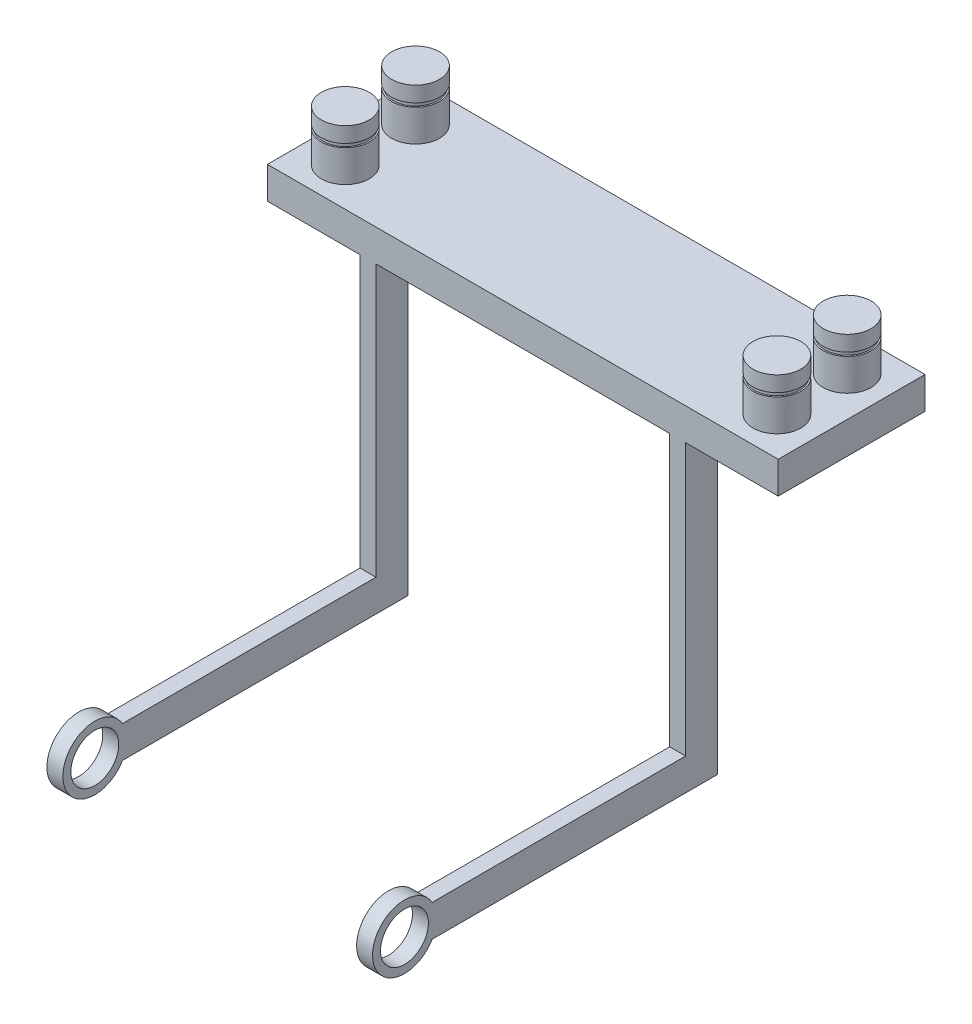
SolidWorks part; units mm, degrees
ref_plane "Front Plane" through (0, 0, 0) normal (0, 0, 1) x (1, 0, 0)
ref_plane "Top Plane" through (0, 0, 0) normal (0, 1, 0) x (1, 0, 0)
ref_plane "Right Plane" through (0, 0, 0) normal (1, 0, 0) x (0, 0, -1)
sketch "Sketch2" plane through (0, 0, 0) normal (0, 1, 0) x (1, 0, 0)
  line L1 (0, 0) -> (50.8, 0)
  line L2 (0, 0) -> (0, 29.21)
  line L3 (0, 29.21) -> (50.8, 29.21)
  line L4 (50.8, 0) -> (50.8, 29.21)
  dimension "D1" = 29.21
  dimension "D2" = 50.8
extrude "Boss-Extrude1" add sketch "Sketch2" along normal blind 6.35
sketch "Sketch4" plane through (0, 6.35, 0) normal (0, 1, 0) x (1, 0, 0)
  line L0 (0, 0) -> (50.8, 0) construction
  line L1 (50.8, 29.21) -> (0, 29.21) construction
  line L2 (50.8, 0) -> (50.8, 29.21) construction
  circle A0 centre (42.926, 7.62) radius 4.7625
  circle A1 centre (42.926, 21.59) radius 4.7625
  dimension "D1" = 9.525
  dimension "D2" = 9.525
  dimension "D3" = 7.62
  dimension "D4" = 7.62
  dimension "D5" = 7.874
  dimension "D6" = 7.874
extrude "Boss-Extrude2" add sketch "Sketch4" along normal blind 6.35
sketch "Sketch7" plane through (0, 12.7, 0) normal (0, 1, 0) x (1, 0, 0)
  line L0 (50.8, 29.21) -> (0, 29.21) construction
  line L1 (0, 0) -> (50.8, 0) construction
  line L2 (50.8, 0) -> (50.8, 29.21) construction
  circle A0 centre (42.926, 21.59) radius 4.4704
  circle A1 centre (42.926, 7.62) radius 4.4704
  dimension "D1" = 8.9408
  dimension "D2" = 8.9408
  dimension "D3" = 7.62
  dimension "D5" = 7.874
  dimension "D6" = 7.874
  dimension "D4" = 7.62
extrude "Boss-Extrude3" add sketch "Sketch7" along normal blind 0.7366
sketch "Sketch8" plane through (0, 13.4366, 0) normal (0, 1, 0) x (1, 0, 0)
  line L0 (50.8, 0) -> (50.8, 29.21) construction
  line L1 (50.8, 29.21) -> (0, 29.21) construction
  circle A0 centre (42.926, 21.59) radius 4.7625
  circle A1 centre (42.926, 7.62) radius 4.7625
  dimension "D1" = 9.525
  dimension "D2" = 9.525
  dimension "D3" = 7.874
  dimension "D4" = 7.62
extrude "Boss-Extrude4" add sketch "Sketch8" along normal blind 3.0734
sketch "Sketch11" plane through (0, 0, 0) normal (0, -1, 0) x (1, 0, 0)
  line L0 (0, -29.21) -> (0, 0) construction
  line L1 (29.21, 0) -> (32.385, 0)
  line L2 (29.21, 0) -> (29.21, -6.35)
  line L3 (29.21, -6.35) -> (32.385, -6.35)
  line L4 (32.385, 0) -> (32.385, -6.35)
  line L5 (0, 0) -> (50.8, 0) construction
  dimension "D1" = 6.35
  dimension "D2" = 3.175
  dimension "D3" = 29.21
  dimension "D4" = 0
extrude "Boss-Extrude5" add sketch "Sketch11" along normal blind 60.325
sketch "Sketch12" plane through (0, 0, 0) normal (0, 0, 1) x (1, 0, 0)
  line L0 (32.385, -60.325) -> (32.385, 0) construction
  line L1 (29.21, -60.325) -> (32.385, -60.325)
  line L2 (29.21, -60.325) -> (29.21, -53.975)
  line L3 (29.21, -53.975) -> (32.385, -53.975)
  line L4 (32.385, -60.325) -> (32.385, -53.975)
  dimension "D1" = 6.35
extrude "Boss-Extrude6" add sketch "Sketch12" along normal blind 55.9194
sketch "Sketch13" plane through (29.21, 0, 0) normal (-1, 0, 0) x (0, 0, 1)
  line L0 (55.9194, -53.975) -> (55.9194, -60.325) construction
  circle A0 centre (55.9194, -57.15) radius 6.35
  circle A1 centre (55.9194, -57.15) radius 4.7625
  dimension "D1" = 12.7
  dimension "D2" = 9.525
extrude "Boss-Extrude8" add sketch "Sketch13" against normal blind 3.175
sketch "Sketch17" plane through (29.21, 0, 0) normal (-1, 0, 0) x (0, 0, 1)
  line L0 (55.9194, -53.975) -> (55.9194, -60.325) construction
  circle A0 centre (55.9194, -57.15) radius 4.7625
  dimension "D1" = 9.525
extrude "Cut-Extrude3" cut sketch "Sketch17" against normal blind 3.175
mirror "Mirror3" about plane through (0, 0, 0) normal (1, 0, 0) of "Boss-Extrude1", "Boss-Extrude2", "Boss-Extrude3", "Boss-Extrude4", "Boss-Extrude5", "Boss-Extrude6", "Boss-Extrude8", "Cut-Extrude3"
